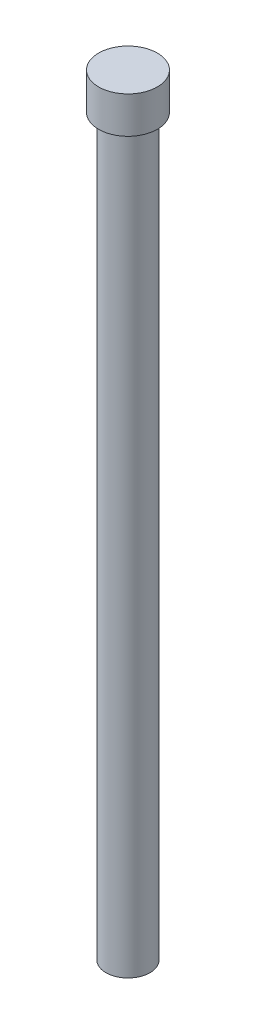
SolidWorks part; units mm, degrees
material "Stainless Steel (ferritic)"
ref_plane "Front Plane" through (0, 0, 0) normal (0, 0, 1) x (1, 0, 0)
ref_plane "Top Plane" through (0, 0, 0) normal (0, 1, 0) x (1, 0, 0)
ref_plane "Right Plane" through (0, 0, 0) normal (1, 0, 0) x (0, 0, -1)
sketch "Sketch1" plane through (0, 0, 0) normal (0, 1, 0) x (1, 0, 0)
  circle A0 centre (0, 0) radius 0.762
  dimension "D1" = 1.524
extrude "Boss-Extrude1" add sketch "Sketch1" along normal blind 25.4
sketch "Sketch2" plane through (0, 25.4, 0) normal (0, 1, 0) x (1, 0, 0)
  circle A0 centre (0, 0) radius 1.016
extrude "Boss-Extrude2" add sketch "Sketch2" along normal blind 1.27
